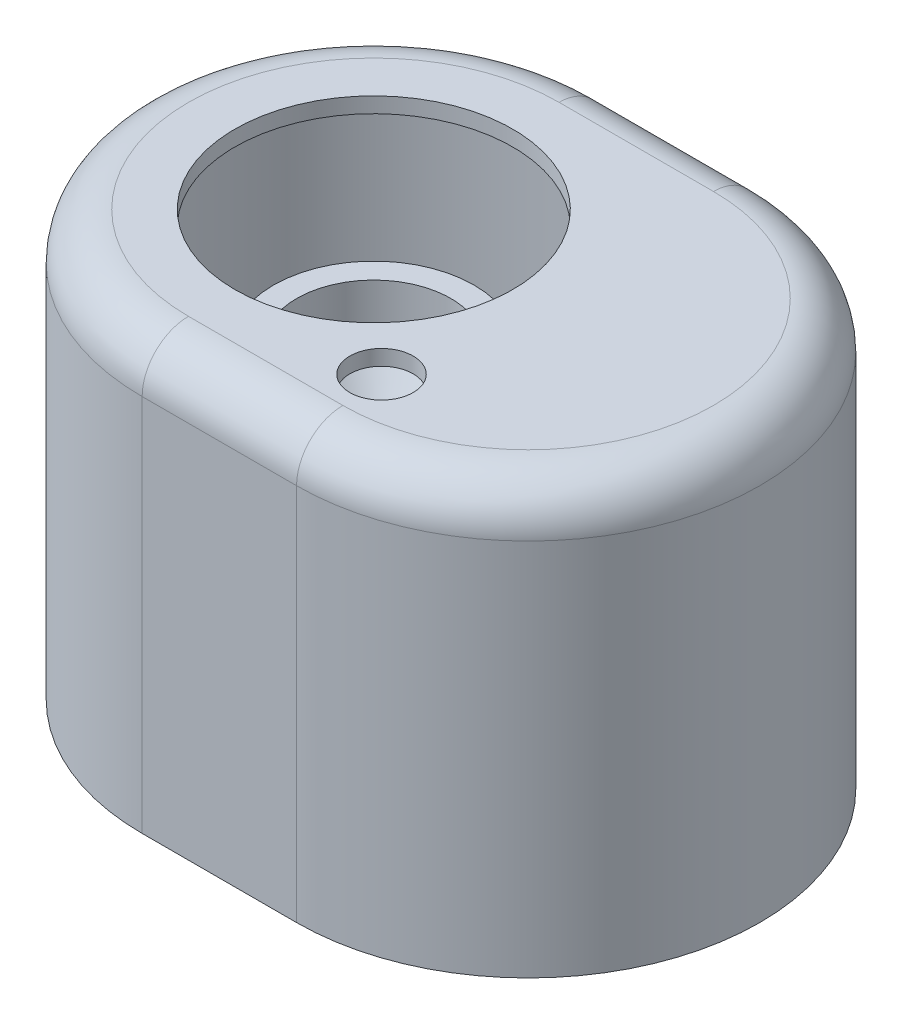
SolidWorks part; units mm, degrees
ref_plane "前视基准面" through (0, 0, 0) normal (0, 0, 1) x (1, 0, 0)
ref_plane "上视基准面" through (0, 0, 0) normal (0, 1, 0) x (1, 0, 0)
ref_plane "右视基准面" through (0, 0, 0) normal (1, 0, 0) x (0, 0, -1)
other "Configuration Table"
sketch "草图2" plane through (0, 0, 0) normal (0, 1, 0) x (1, 0, 0)
  line L0 (0, 0) -> (20, 0) construction
  line L1 (0, 30) -> (20, 30)
  line L2 (0, -30) -> (20, -30)
  arc A0 (0, 30) -> (0, -30) centre (0, 0) ccw
  arc A1 (20, -30) -> (20, 30) centre (20, 0) ccw
  point P3 (10, 0)
  point P8 (0, 0)
  dimension "D1" = 60
  dimension "D2" = 20
extrude "凸台-拉伸1" add sketch "草图2" along normal blind 55
fillet "圆角1" radius 6 4 edges at (10, 55, -30) (50, 55, 0) (10, 55, 30) (-30, 55, 0)
shell "抽壳3" thickness 2
sketch "草图3" plane through (0, 55, 0) normal (0, 1, 0) x (1, 0, 0)
  circle A0 centre (0, 0) radius 18
  dimension "D1" = 36
extrude "切除-拉伸1" cut sketch "草图3" against normal through all contours A0
sketch "草图5" plane through (0, 0, 0) normal (0, 0, 1) x (1, 0, 0)
  line L0 (0, 40) -> (0, 12.3001) construction
  line L1 (0, 49) -> (0, 0) construction
  line L2 (0, 40) -> (-10, 40) construction
  line L3 (-10, 40) -> (-10, 34.4373)
  line L4 (-10, 34.4373) -> (-8, 34.4373)
  line L5 (-8, 34.4373) -> (-8, 32.4373)
  line L6 (-8, 32.4373) -> (-4.5, 27.4373)
  line L7 (-4.5, 27.4373) -> (-4.5, 25.4373)
  line L8 (-4.5, 25.4373) -> (-6.5, 25.4373)
  line L9 (-6.5, 25.4373) -> (-6.5, 21.4373)
  line L10 (-6.5, 21.4373) -> (-9.5, 21.4373)
  line L11 (-9.5, 21.4373) -> (-9.5, 29)
  line L12 (-9.5, 29) -> (-13, 34)
  line L13 (-13, 34) -> (-13, 40)
  line L14 (-13, 40) -> (-10, 40)
  line L15 (18, 55) -> (-18, 55) construction
  dimension "D1" = 20
  dimension "D2" = 2
  dimension "D3" = 13
  dimension "D4" = 4
  dimension "D5" = 3
  dimension "D6" = 9
  dimension "D7" = 6
  dimension "D8" = 3.2
  dimension "D9" = 2
  dimension "D10" = 3
  dimension "D11" = 15
  dimension "D12" = 2
revolve "旋转1" add sketch "草图5" angle 360 about L0
ref_plane "基准面1" through (0, 26.54, 0) normal (0, -1, 0) x (-1, 0, 0)
sketch "草图6" plane through (0, 26.54, 0) normal (0, -1, 0) x (-1, 0, 0)
  line L0 (-31, -19.5) -> (-31, -31.2539) construction
  line L1 (-27.85, -19.5) -> (-27.85, -31.2539)
  line L2 (-34.15, -19.5) -> (-34.15, -31.2539)
  line L3 (-31, 19.5) -> (-31, 31.2539) construction
  line L4 (-34.15, 19.5) -> (-34.15, 31.2539)
  line L5 (-27.85, 19.5) -> (-27.85, 31.2539)
  arc A0 (-27.85, -19.5) -> (-34.15, -19.5) centre (-31, -19.5) ccw
  arc A1 (-34.15, -31.2539) -> (-27.85, -31.2539) centre (-31, -31.2539) ccw
  arc A2 (-34.15, 19.5) -> (-27.85, 19.5) centre (-31, 19.5) ccw
  arc A3 (-27.85, 31.2539) -> (-34.15, 31.2539) centre (-31, 31.2539) ccw
  circle A4 centre (-31, -19.5) radius 1.5 construction
  arc A5 (-20, 30) -> (-20, -30) centre (-20, 0) ccw construction
  arc A6 (-20, 30) -> (-20, -30) centre (-20, 0) ccw
  point P2 (-31, -25.377)
  point P10 (-31, 25.377)
  point P15 (0, 0)
  point P16 (-31.6309, -23.1981)
  point P17 (-32.7409, -23.5)
  point P18 (0, 0)
  point P19 (-28.1739, -23.7055)
  dimension "D1" = 6.3
extrude "凸台-拉伸2" add sketch "草图6" against normal up to body contours L5 A6 L4 A2 | L2 A6 L1 A0
sketch "草图7" plane through (0, 55, 0) normal (0, 1, 0) x (1, 0, 0)
  circle A0 centre (19, -18) radius 4.1
  point P3 (0, 0)
  point P8 (3.5487, 0.9903)
  dimension "D1" = 8.2
  dimension "D2" = 19
  dimension "D3" = 18
extrude "切除-拉伸2" cut sketch "草图7" against normal through all
sketch "草图8" plane through (0, 0, 0) normal (0, -1, 0) x (1, 0, 0)
  line L0 (20, 28) -> (0, 28) construction
  line L1 (20, 28) -> (0, 28)
  line L2 (0, -30) -> (20, -30)
  line L3 (20, 30) -> (0, 30)
  line L4 (0, -30) -> (20, -30)
  line L5 (20, 30) -> (0, 30)
  line L6 (0, -28) -> (20, -28) construction
  line L7 (0, -28) -> (20, -28)
  line L8 (20, 28) -> (0, 28)
  line L9 (0, -26.5) -> (20, -26.5)
  line L10 (20, 26.5) -> (0, 26.5)
  arc A0 (0, 28) -> (0, -28) centre (0, 0) ccw construction
  arc A1 (20, -28) -> (20, 28) centre (20, 0) ccw construction
  arc A2 (0, 30) -> (0, -30) centre (0, 0) ccw
  arc A3 (20, -30) -> (20, 30) centre (20, 0) ccw
  arc A4 (0, 30) -> (0, -30) centre (0, 0) ccw
  arc A5 (20, -30) -> (20, 30) centre (20, 0) ccw
  arc A6 (0, 28) -> (0, -28) centre (0, 0) ccw
  arc A7 (20, -28) -> (20, 28) centre (20, 0) ccw
  arc A8 (0, 26.5) -> (0, -26.5) centre (0, 0) ccw
  arc A9 (20, -26.5) -> (20, 26.5) centre (20, 0) ccw
  line M6 (20, -28) -> (0, -28)
  arc M7 (0, -28) -> (0, 28) centre (0, 0) cw
  line M8 (0, 28) -> (20, 28)
  arc M9 (20, 28) -> (20, -28) centre (20, 0) cw
  dimension "D1" = 0
extrude "凸台-拉伸3" add sketch "草图8" against normal blind 4 from offset 2 contours A9 L9 A8 L10 M6 M9 M8 M7
